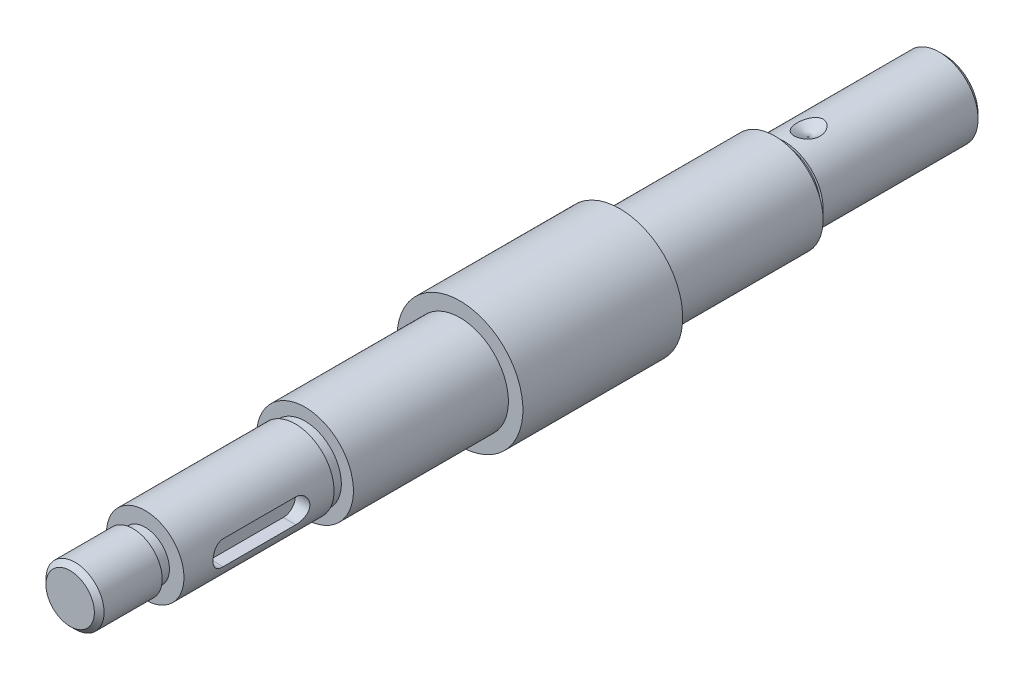
SolidWorks part; units mm, degrees
ref_plane "前视基准面" through (0, 0, 0) normal (0, 0, 1) x (1, 0, 0)
ref_plane "上视基准面" through (0, 0, 0) normal (0, 1, 0) x (1, 0, 0)
ref_plane "右视基准面" through (0, 0, 0) normal (1, 0, 0) x (0, 0, -1)
other "Configuration Table"
sketch "草图1" plane through (0, 0, 0) normal (0, 0, 1) x (1, 0, 0)
  circle A0 centre (0, 0) radius 6
extrude "凸台-拉伸1" add sketch "草图1" against normal blind 13
cosmetic thread "装饰螺纹线1" parameters "D2"=11
sketch "草图2" plane through (0, 0, -13) normal (0, 0, -1) x (-1, 0, 0)
  circle A0 centre (0, 0) radius 5
extrude "凸台-拉伸2" add sketch "草图2" along normal blind 2.5
sketch "草图3" plane through (0, 0, -15.5) normal (0, 0, -1) x (-1, 0, 0)
  circle A0 centre (0, 0) radius 8
extrude "凸台-拉伸3" add sketch "草图3" along normal blind 31
sketch "草图4" plane through (0, 0, -46.5) normal (0, 0, -1) x (-1, 0, 0)
  circle A0 centre (0, 0) radius 7.5
extrude "凸台-拉伸4" add sketch "草图4" along normal blind 2
sketch "草图5" plane through (0, 0, -48.5) normal (0, 0, -1) x (-1, 0, 0)
  circle A0 centre (0, 0) radius 10
extrude "凸台-拉伸5" add sketch "草图5" along normal blind 32
sketch "草图6" plane through (0, 0, -80.5) normal (0, 0, -1) x (-1, 0, 0)
  circle A0 centre (0, 0) radius 13
extrude "凸台-拉伸6" add sketch "草图6" along normal blind 33
sketch "草图7" plane through (0, 0, -113.5) normal (0, 0, -1) x (-1, 0, 0)
  circle A0 centre (0, 0) radius 10
extrude "凸台-拉伸7" add sketch "草图7" along normal blind 32
sketch "草图8" plane through (0, 0, -145.5) normal (0, 0, -1) x (-1, 0, 0)
  circle A0 centre (0, 0) radius 7.5
extrude "凸台-拉伸8" add sketch "草图8" along normal blind 2
sketch "草图9" plane through (0, 0, -147.5) normal (0, 0, -1) x (-1, 0, 0)
  circle A0 centre (0, 0) radius 8
extrude "凸台-拉伸9" add sketch "草图9" along normal blind 33
ref_plane "基准面1" through (8, 0, 0) normal (1, 0, 0) x (0, 0, -1)
sketch "草图11" plane through (8, 0, 0) normal (1, 0, 0) x (0, 0, -1)
  line L1 (24, 2.5) -> (39, 2.5)
  line L2 (24, -2.5) -> (39, -2.5)
  arc A0 (24, -2.5) -> (24, 2.5) centre (24, 0) cw
  arc A1 (39, 2.5) -> (39, -2.5) centre (39, 0) cw
  dimension "D2" = 2.5
extrude "切除-拉伸1" cut sketch "草图11" against normal blind 3
ref_plane "基准面2" through (0, -8, 0) normal (0, 1, 0) x (1, 0, 0)
sketch "草图12" plane through (0, -8, 0) normal (0, 1, 0) x (1, 0, 0)
  line L1 (-2.5, 168) -> (-2.5, 153)
  line L2 (2.5, 168) -> (2.5, 153)
  line L3 (10, 145.5) -> (-10, 145.5) construction
  arc A0 (-2.5, 168) -> (2.5, 168) centre (0, 168) cw
  arc A1 (-2.5, 153) -> (2.5, 153) centre (0, 153) ccw
  point P9 (0, 150.5)
  point P13 (0, 170.5)
  dimension "D3" = 2.5
  dimension "D4" = 2.5
  dimension "D1" = 5
  dimension "D2" = 20
extrude "切除-拉伸2" cut sketch "草图12" along normal blind 3
sketch "草图18" plane through (0, 0, 0) normal (1, 0, 0) x (0, 0, -1)
  line L0 (145.5, -10) -> (145.5, 10) construction
  line L1 (149.5, 8) -> (152.5, 8)
  line L2 (180.5, 8) -> (147.5, 8) construction
  line L5 (152.5, 6.2679) -> (149.5, 8)
  line L6 (152.5, 8) -> (152.5, 6.2679)
  dimension "D1" = 3
  dimension "D2" = 30
  dimension "D3" = 7
revolve "切除-旋转1" cut sketch "草图18" angle 360 about L6
chamfer "倒角1" distance 1 angle 45 2 edges at (6, 0, 0) (-8, 0, -180.5)
